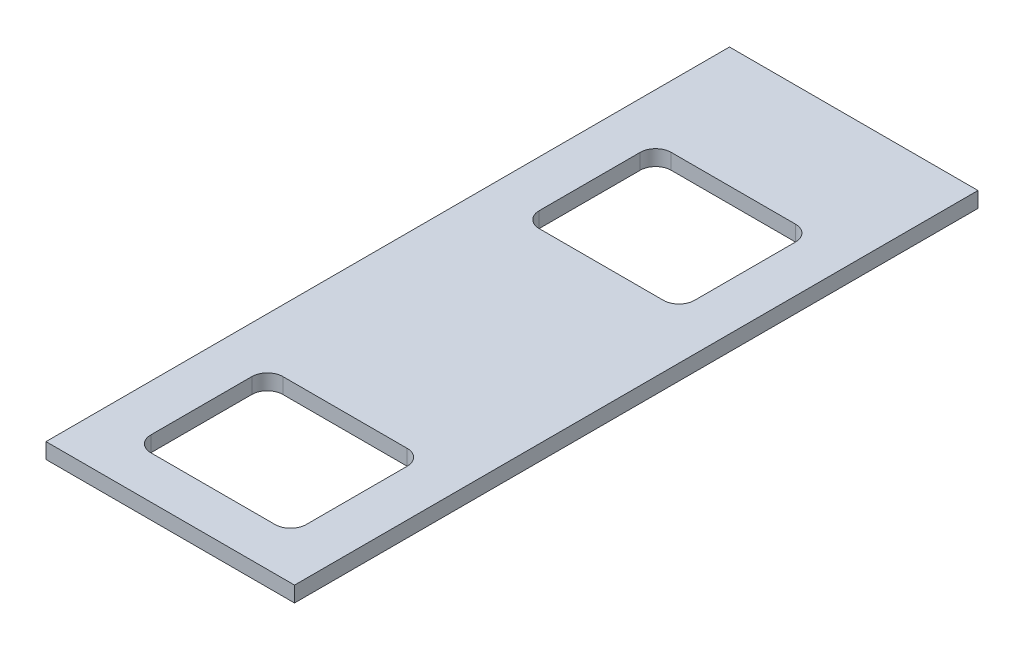
SolidWorks part; units mm, degrees
material "6061-T6 (SS)"
ref_plane "Front Plane" through (0, 0, 0) normal (0, 0, 1) x (1, 0, 0)
ref_plane "Top Plane" through (0, 0, 0) normal (0, 1, 0) x (1, 0, 0)
ref_plane "Right Plane" through (0, 0, 0) normal (1, 0, 0) x (0, 0, -1)
sketch "Sketch1" plane through (0, 0, 0) normal (0, 0, 1) x (1, 0, 0)
  line L1 (-25.4, -25.4) -> (25.4, -25.4)
  line L2 (-25.4, -25.4) -> (-25.4, 25.4)
  line L3 (-25.4, 25.4) -> (25.4, 25.4)
  line L4 (25.4, -25.4) -> (25.4, 25.4)
  line L5 (-25.4, -25.4) -> (25.4, 25.4) construction
  line L6 (-25.4, 25.4) -> (25.4, -25.4) construction
  point P0 (0, 0)
  dimension "D1" = 50.8
  dimension "D2" = 50.8
extrude "Boss-Extrude1" add sketch "Sketch1" along normal mid plane 139.7
shell "Shell1" thickness 3.175
sketch "Sketch2" plane through (0, 0, 0) normal (0, 1, 0) x (1, 0, 0)
  line L0 (25.4, 69.85) -> (-25.4, 69.85) construction
  line L1 (15.875, 45.2437) -> (-15.875, 45.2437)
  line L2 (15.875, 45.2437) -> (15.875, 18.2563)
  line L3 (15.875, 18.2563) -> (-15.875, 18.2563)
  line L4 (-15.875, 45.2437) -> (-15.875, 18.2563)
  line L5 (25.4, -69.85) -> (-25.4, -69.85) construction
  line L7 (15.875, -34.1313) -> (-15.875, -34.1313)
  line L8 (15.875, -34.1313) -> (15.875, -61.1187)
  line L9 (15.875, -61.1187) -> (-15.875, -61.1187)
  line L10 (-15.875, -34.1313) -> (-15.875, -61.1187)
  point P4 (0, 45.2437)
  point P7 (0, 69.85)
  point P9 (15.875, 31.75)
  point P15 (0, -69.85)
  point P16 (0, -61.1187)
  point P17 (-15.875, -47.625)
  dimension "D1" = 31.75
  dimension "D2" = 26.9875
  dimension "D3" = 101.6
  dimension "D4" = 22.225
extrude "Cut-Extrude1" cut sketch "Sketch2" along normal through all
fillet "Fillet1" radius 3.175 4 edges at (15.875, 23.8125, -45.2437) (-15.875, 23.8125, -45.2437) (-15.875, 23.8125, -18.2563) (15.875, 23.8125, -18.2563)
sketch "Sketch3" plane through (0, 0, 0) normal (1, 0, 0) x (0, 0, -1)
  line L1 (-69.85, 25.4) -> (-69.85, -25.4) construction
  line L2 (-69.85, 25.4) -> (69.85, 25.4) construction
  circle A0 centre (31.75, 9.525) radius 3.175
  circle A1 centre (-44.45, 9.525) radius 3.175
  dimension "D1" = 6.35
  dimension "D2" = 25.4
  dimension "D3" = 76.2
  dimension "D4" = 15.875
extrude "Cut-Extrude2" cut sketch "Sketch3" against normal through all both and the other way through all
sketch "Sketch4" plane through (0, 0, 0) normal (1, 0, 0) x (0, 0, -1)
  line L0 (-69.85, 25.4) -> (69.85, 25.4) construction
  line L1 (69.85, 25.4) -> (69.85, -25.4) construction
  line L2 (-69.85, 25.4) -> (-69.85, -25.4) construction
  circle A0 centre (57.15, 12.7) radius 2.4892
  circle A1 centre (44.45, 12.7) radius 2.4892 construction
  circle A2 centre (31.75, 12.7) radius 2.4892 construction
  circle A3 centre (19.05, 12.7) radius 2.4892 construction
  circle A10 centre (44.45, 0) radius 2.4892 construction
  circle A11 centre (31.75, 0) radius 2.4892 construction
  circle A12 centre (19.05, 0) radius 2.4892 construction
  circle A19 centre (44.45, -12.7) radius 2.4892
  circle A20 centre (31.75, -12.7) radius 2.4892
  circle A21 centre (19.05, -12.7) radius 2.4892
  circle A28 centre (57.15, 0) radius 2.4892
  circle A29 centre (57.15, -12.7) radius 2.4892
  circle A30 centre (-61.9125, 12.7) radius 2.4892
  circle A31 centre (-49.2125, 12.7) radius 2.4892 construction
  circle A32 centre (-36.5125, 12.7) radius 2.4892 construction
  circle A33 centre (-23.8125, 12.7) radius 2.4892 construction
  circle A34 centre (-11.1125, 12.7) radius 2.4892
  circle A35 centre (1.5875, 12.7) radius 2.4892 construction
  circle A36 centre (-49.2125, 0) radius 2.4892 construction
  circle A37 centre (-36.5125, 0) radius 2.4892 construction
  circle A38 centre (-23.8125, 0) radius 2.4892 construction
  circle A39 centre (-11.1125, 0) radius 2.4892 construction
  circle A40 centre (1.5875, 0) radius 2.4892 construction
  circle A41 centre (-49.2125, -12.7) radius 2.4892 construction
  circle A42 centre (-36.5125, -12.7) radius 2.4892
  circle A43 centre (-23.8125, -12.7) radius 2.4892 construction
  circle A44 centre (-11.1125, -12.7) radius 2.4892
  circle A45 centre (1.5875, -12.7) radius 2.4892 construction
  circle A46 centre (-61.9125, 0) radius 2.4892 construction
  circle A47 centre (-61.9125, -12.7) radius 2.4892
  dimension "D1" = 4.9784
  dimension "D3" = 12.7
  dimension "D8" = 4.9784
  dimension "D9" = 7.9375
  dimension "D14" = 12.7
  dimension "D2" = 12.7
  dimension "D6" = 12.7
  dimension "D7" = 12.7
  dimension "D10" = 12.7
  dimension "D13" = 12.7
  dimension "D4" = 4
  dimension "D5" = 3
  dimension "D11" = 6
  dimension "D12" = 3
extrude "Cut-Extrude3" cut sketch "Sketch4" against normal through all both and the other way through all
sketch "Sketch5" plane through (0, 0, 0) normal (0, 1, 0) x (1, 0, 0)
  line L1 (25.4, -69.85) -> (-25.4, -69.85) construction
  line L2 (-25.4, -69.85) -> (-25.4, 69.85) construction
  circle A0 centre (-12.7, -57.15) radius 2.4892
  circle A1 centre (0, -57.15) radius 2.4892
  circle A2 centre (12.7, -57.15) radius 2.4892
  dimension "D1" = 4.9784
  dimension "D3" = 12.7
  dimension "D2" = 12.7
  dimension "D5" = 12.7
  dimension "D4" = 3
extrude "Cut-Extrude4" cut sketch "Sketch5" against normal through all and the other way through all
fillet "Fillet2" radius 3.175 4 edges at (-15.875, 23.8125, 34.1313) (-15.875, 23.8125, 61.1187) (15.875, 23.8125, 61.1187) (15.875, 23.8125, 34.1313)
sketch "Sketch6" plane through (25.4, 0, 0) normal (1, 0, 0) x (0, 0, -1)
  line L0 (69.85, -25.4) -> (69.85, 25.4) construction
  line L1 (-69.85, -25.4) -> (69.85, -25.4)
  line L2 (-69.85, -25.4) -> (-69.85, 22.225)
  line L3 (-69.85, 22.225) -> (69.85, 22.225)
  line L4 (69.85, -25.4) -> (69.85, 22.225)
  line L5 (-69.85, 25.4) -> (69.85, 25.4) construction
  dimension "D1" = 3.175
extrude "Cut-Extrude5" cut sketch "Sketch6" against normal through all
